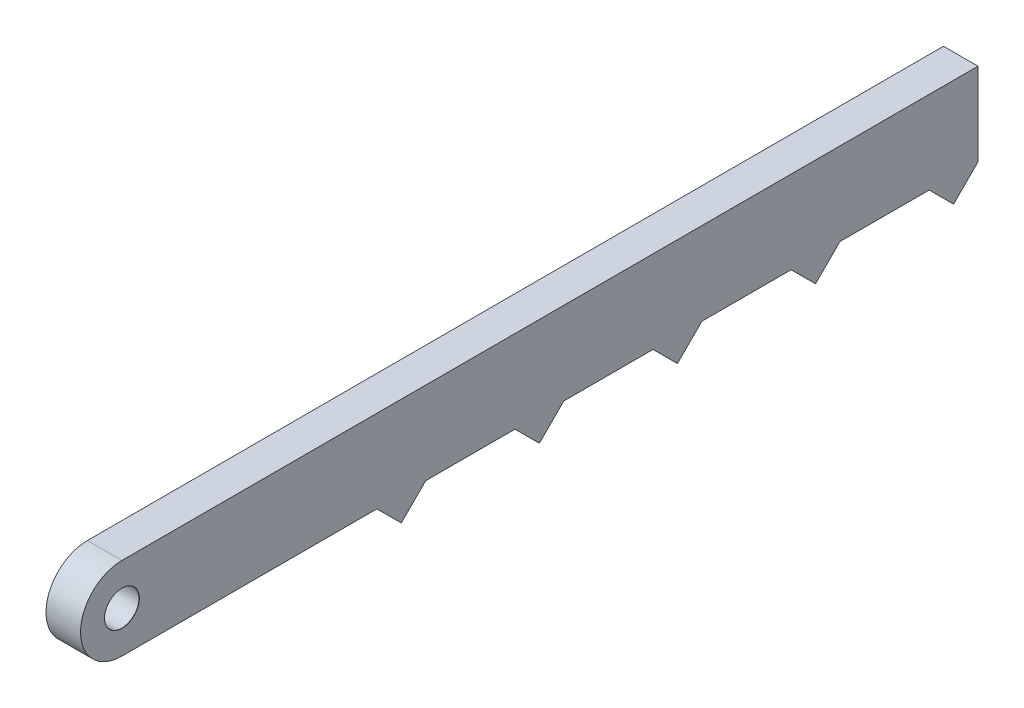
SolidWorks part; units mm, degrees
ref_plane "Front Plane" through (0, 0, 0) normal (0, 0, 1) x (1, 0, 0)
ref_plane "Top Plane" through (0, 0, 0) normal (0, 1, 0) x (1, 0, 0)
ref_plane "Right Plane" through (0, 0, 0) normal (1, 0, 0) x (0, 0, -1)
sketch "Sketch1" plane through (0, 0, 0) normal (1, 0, 0) x (0, 0, -1)
  line L0 (0, 0) -> (130, 0)
  line L1 (55, 0) -> (-55, 0) construction
  line L2 (130, 0) -> (130, -12)
  line L3 (130, -12) -> (0, -12)
  line L4 (0, 55) -> (0, -55) construction
  line L5 (0, -12) -> (0, 0)
extrude "Boss-Extrude1" add sketch "Sketch1" along normal blind 5
sketch "Sketch2" plane through (5, 0, 0) normal (1, 0, 0) x (0, 0, -1)
  line L0 (130, -12) -> (126.4645, -15.5355)
  line L1 (126.4645, -15.5355) -> (122.9289, -12)
  line L2 (106.4645, -15.5355) -> (102.9289, -12)
  line L3 (110, -12) -> (106.4645, -15.5355)
  line L4 (0, -12) -> (130, -12) construction
  line L5 (86.4645, -15.5355) -> (82.9289, -12)
  line L6 (90, -12) -> (86.4645, -15.5355)
  line L7 (66.4645, -15.5355) -> (62.9289, -12)
  line L8 (70, -12) -> (66.4645, -15.5355)
  line L9 (46.4645, -15.5355) -> (42.9289, -12)
  line L10 (50, -12) -> (46.4645, -15.5355)
  line L11 (122.9289, -12) -> (130, -12)
  line L12 (102.9289, -12) -> (110, -12)
  line L13 (82.9289, -12) -> (90, -12)
  line L14 (62.9289, -12) -> (70, -12)
  line L15 (42.9289, -12) -> (50, -12)
  dimension "D1" = 5
extrude "Boss-Extrude2" add sketch "Sketch2" against normal blind 5
sketch "Sketch5" plane through (5, 0, 0) normal (1, 0, 0) x (0, 0, -1)
  line L0 (6, 0) -> (0, 0)
  line L1 (0, 0) -> (0, -6)
  line L2 (0, -6) -> (0, -12)
  line L3 (0, 2.75) -> (0, -2.75) construction
  line L4 (0, -12) -> (6, -12)
  arc A0 (6, 0) -> (6, -12) centre (6, -6) ccw
  line M7 (0, 0) -> (0, -12)
  line M8 (0, -12) -> (42.9289, -12)
  line M24 (130, 0) -> (0, 0)
extrude "Cut-Extrude1" cut sketch "Sketch5" against normal through all contours A0 M24 M7 | A0 M7 M8
sketch "Sketch6" plane through (5, 0, 0) normal (1, 0, 0) x (0, 0, -1)
  point P0 (6, -6)
hole_wizard "Ø5.0mm Dowel Hole1" positions "Sketch6" profile "Sketch7" hole size "Ø5.0" standard "ANSI Metric" end condition through all
sketch "Sketch7" plane through (5, -6, -6) normal (0, 1, 0) x (0, 0, -1)
  line L0 (0, 0) -> (0, 5)
  line L1 (0, 5) -> (2.5, 5)
  line L2 (2.5, 5) -> (2.5, 0.025)
  line L3 (2.5, 0.025) -> (2.525, 0)
  line L5 (2.525, 0) -> (0, 0)
  line L6 (-2.5, 0.025) -> (-2.525, 0) construction
  line L11 (0, -6.35) -> (0, 107.95) construction
  dimension "Thru Hole Dia." = 5
  dimension "Thru Hole Depth" = 5
  dimension "Near C'Sink Dia." = 5.05
  dimension "Near C'Sink Angle" = 90
